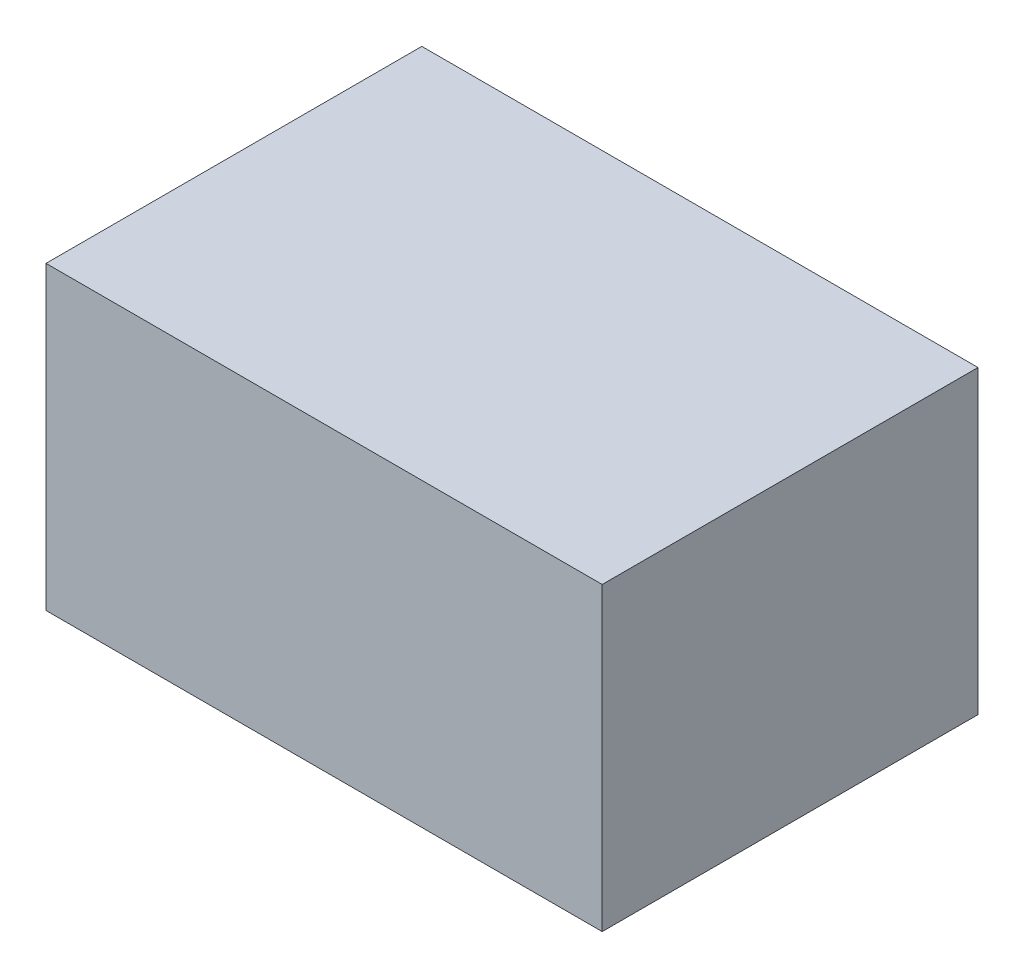
SolidWorks part; units mm, degrees
ref_plane "Front Plane" through (0, 0, 0) normal (0, 0, 1) x (1, 0, 0)
ref_plane "Top Plane" through (0, 0, 0) normal (0, 1, 0) x (1, 0, 0)
ref_plane "Right Plane" through (0, 0, 0) normal (1, 0, 0) x (0, 0, -1)
sketch "Sketch1" plane through (0, 0, 0) normal (1, 0, 0) x (0, 0, -1)
  line L1 (0, 0) -> (50, 0)
  line L2 (0, 0) -> (0, 40)
  line L3 (0, 40) -> (50, 40)
  line L4 (50, 0) -> (50, 40)
  dimension "J" = 50
  dimension "B" = 40
extrude "Boss-Extrude1" add sketch "Sketch1" along normal mid plane 74
